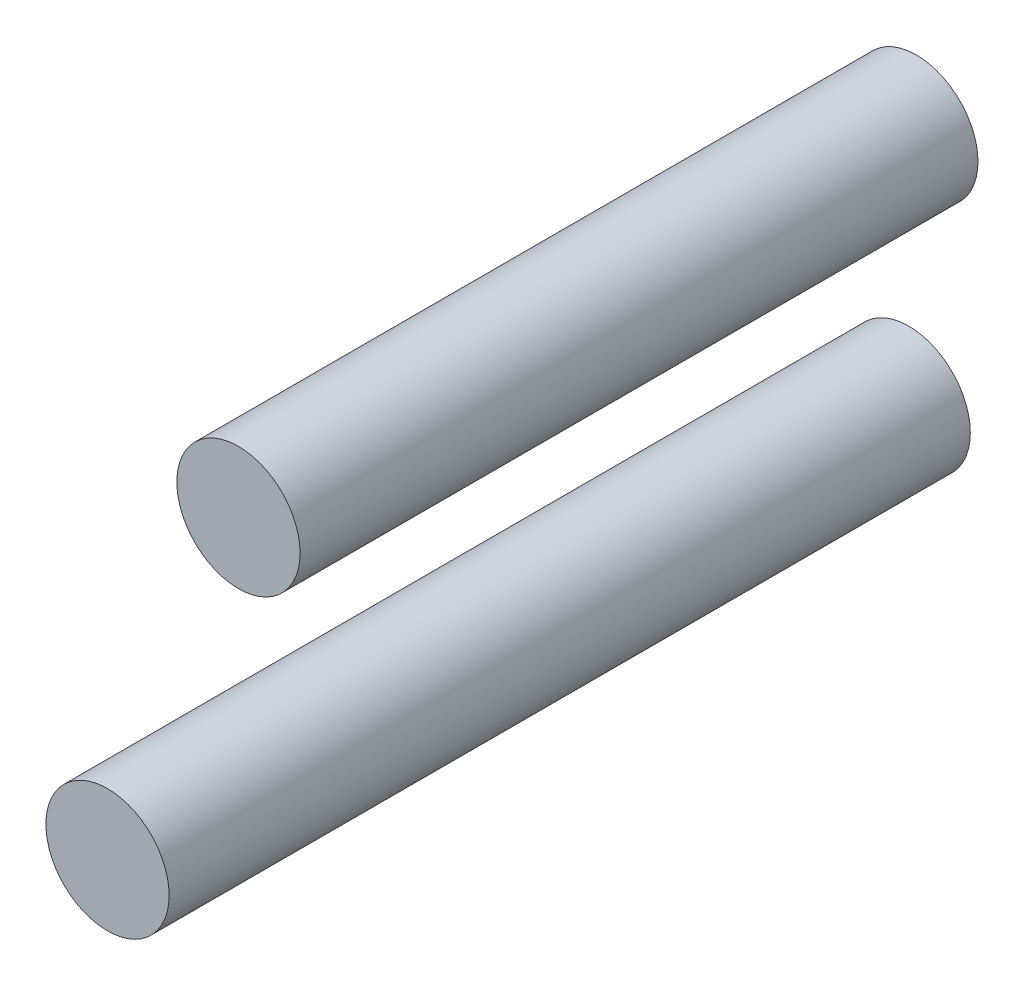
SolidWorks part; units mm, degrees
ref_plane "Płaszczyzna przednia" through (0, 0, 0) normal (0, 0, 1) x (1, 0, 0)
ref_plane "Płaszczyzna górna" through (0, 0, 0) normal (0, 1, 0) x (1, 0, 0)
ref_plane "Płaszczyzna prawa" through (0, 0, 0) normal (1, 0, 0) x (0, 0, -1)
sketch "Szkic1" plane through (0, 0, 0) normal (0, 0, 1) x (1, 0, 0)
  circle A1 centre (-25, 0) radius 10
  dimension "D2" = 20
extrude "Dodanie-wyciągnięcie1" add sketch "Szkic1" along normal mid plane 130 contours A1
sketch "Szkic3" plane through (0, 0, 0) normal (0, 0, 1) x (1, 0, 0)
  circle A0 centre (-13.7524, 48.7185) radius 10
  dimension "D1" = 20
  dimension "D2" = 50
extrude "Dodanie-wyciągnięcie3" add sketch "Szkic3" along normal mid plane 110 separate body
